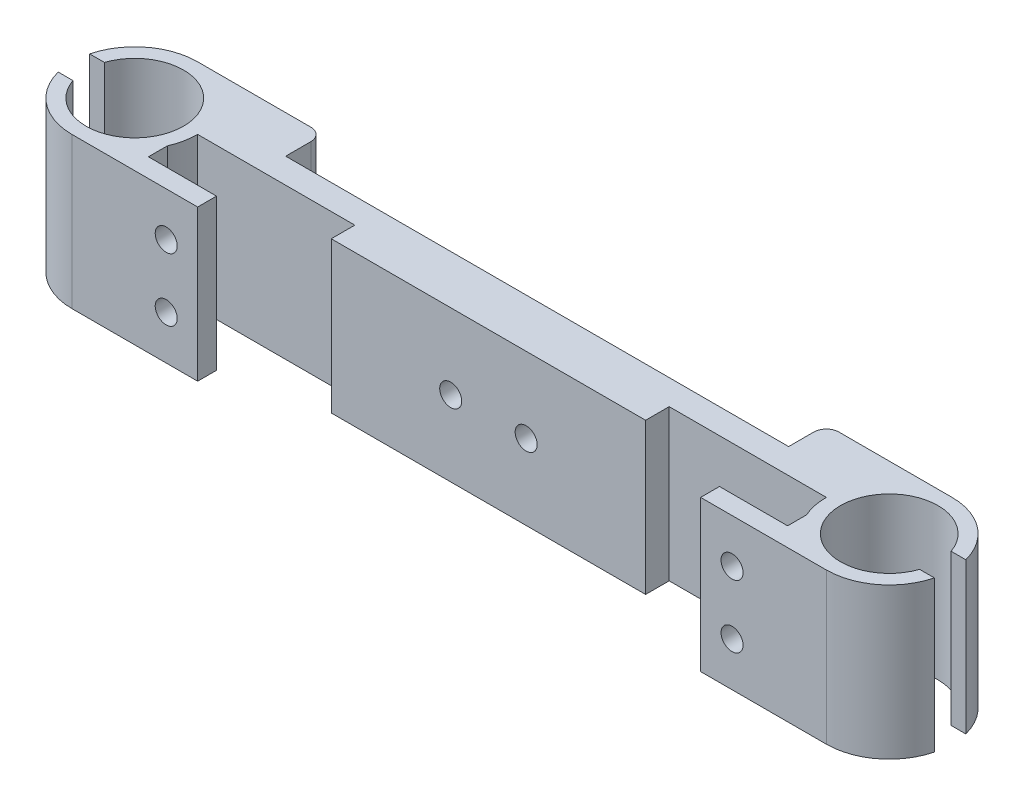
SolidWorks part; units mm, degrees
ref_plane "前视基准面" through (0, 0, 0) normal (0, 0, 1) x (1, 0, 0)
ref_plane "上视基准面" through (0, 0, 0) normal (0, 1, 0) x (1, 0, 0)
ref_plane "右视基准面" through (0, 0, 0) normal (1, 0, 0) x (0, 0, -1)
sketch "草图1" plane through (0, 0, 0) normal (0, 1, 0) x (1, 0, 0)
  line L0 (-50.8348, -4) -> (50.8348, -4)
  line L1 (-60, 0) -> (60, 0) construction
  line L2 (0, 11.701) -> (0, -19.7472) construction
  line L3 (-60, -10) -> (60, -10)
  arc A0 (-50.8348, -4) -> (-60, -10) centre (-60, 0) ccw
  arc A1 (60, -10) -> (50.8348, -4) centre (60, 0) ccw
  circle A2 centre (-60, 0) radius 7.75
  circle A3 centre (60, 0) radius 7.75
  dimension "D1" = 20
  dimension "D2" = 15.5
  dimension "D3" = 120
  dimension "D4" = 15.5
  dimension "D5" = 4
  dimension "D6" = 60
extrude "凸台-拉伸1" add sketch "草图1" along normal blind 24
sketch "草图2" plane through (0, 24, 0) normal (0, 1, 0) x (1, 0, 0)
  line L0 (-50, 0) -> (50, 0)
  line L1 (-60, 10) -> (60, 10)
  arc A0 (-50.8348, -4) -> (-60, -10) centre (-60, 0) ccw construction
  arc A1 (60, -10) -> (50.8348, -4) centre (60, 0) ccw construction
  circle A2 centre (-60, 0) radius 10
  circle A3 centre (60, 0) radius 10
  arc M3 (-50.8348, -4) -> (-60, -10) centre (-60, 0) ccw
  arc M5 (60, -10) -> (50.8348, -4) centre (60, 0) ccw
  dimension "D1" = 20
extrude "凸台-拉伸2" add sketch "草图2" against normal up to surface (24 mm away) contours L1 L0 M3 M5 up to face at (0, 0, -0.6833)
sketch "草图3" plane through (0, 0, 0) normal (0, -1, 0) x (1, 0, 0)
  line L0 (50, 0) -> (-50, 0) construction
  line L1 (25, 0) -> (-25, 0)
  line L2 (25, 0) -> (25, 3.75)
  line L3 (25, 3.75) -> (-25, 3.75)
  line L4 (-25, 0) -> (-25, 3.75)
  dimension "D1" = 50
  dimension "D2" = 25
  dimension "D3" = 3.75
extrude "凸台-拉伸3" add sketch "草图3" against normal blind 24
sketch "草图4" plane through (0, 0, 0) normal (0, -1, 0) x (1, 0, 0)
  line L0 (50.8348, 4) -> (-50.8348, 4) construction
  line L1 (40, 4) -> (-40, 4)
  line L2 (40, 4) -> (40, 10)
  line L3 (40, 10) -> (-40, 10)
  line L4 (-40, 4) -> (-40, 10)
  line L5 (-60, 10) -> (60, 10) construction
  line L6 (60, -10) -> (-60, -10) construction
  line L7 (40, -10) -> (-40, -10)
  line L8 (40, -10) -> (40, -4)
  line L9 (40, -4) -> (-40, -4)
  line L10 (-40, -10) -> (-40, -4)
  line L11 (-25, 0) -> (-50, 0) construction
  dimension "D1" = 80
  dimension "D2" = 40
  dimension "D3" = 80
  dimension "D4" = 4
extrude "切除-拉伸1" cut sketch "草图4" against normal blind 24
fillet "圆角1" radius 2 2 edges at (-40, 12, -10) (40, 12, -10)
sketch "草图5" plane through (0, 0, 0) normal (0, -1, 0) x (1, 0, 0)
  line L0 (67.75, 0) -> (-70, 0) construction
  line L1 (0, -0.3543) -> (0, -8.2573) construction
  line L2 (72.0018, -2.5) -> (64.249, -2.5)
  line L3 (72.0018, -2.5) -> (72.0018, 2.5)
  line L4 (72.0018, 2.5) -> (64.249, 2.5)
  line L5 (64.249, -2.5) -> (64.249, 2.5)
  line L6 (-64.249, -2.5) -> (-64.249, 2.5)
  line L7 (-72.0018, 2.5) -> (-64.249, 2.5)
  line L8 (-72.0018, -2.5) -> (-72.0018, 2.5)
  line L9 (-72.0018, -2.5) -> (-64.249, -2.5)
  circle A0 centre (60, 0) radius 7.75 construction
  arc A1 (-60, 10) -> (-60, -10) centre (-60, 0) ccw construction
  dimension "D1" = 5
  dimension "D2" = 2.5
extrude "切除-拉伸2" cut sketch "草图5" against normal blind 24
sketch "草图6" plane through (0, 0, -4) normal (0, 0, -1) x (-1, 0, 0)
  line L0 (-40, 0) -> (40, 0) construction
  circle A0 centre (-6, 12) radius 1.75
  circle A1 centre (6, 12) radius 1.75
  dimension "D1" = 3.5
  dimension "D2" = 3.5
  dimension "D3" = 12
  dimension "D4" = 12
  dimension "D5" = 12
  dimension "D6" = 6
extrude "切除-拉伸3" cut sketch "草图6" against normal blind 24
sketch "草图7" plane through (0, 0, 10) normal (0, 0, 1) x (1, 0, 0)
  line L0 (40, 24) -> (40, 0) construction
  circle A0 centre (45, 7) radius 1.75
  circle A1 centre (45, 17) radius 1.75
  point P6 (40, 12)
  dimension "D1" = 10
  dimension "D2" = 5
  dimension "D3" = 5
  dimension "D4" = 3.5
  dimension "D5" = 3.5
extrude "切除-拉伸4" cut sketch "草图7" against normal blind 3
sketch "草图8" plane through (0, 0, 0) normal (0, -1, 0) x (1, 0, 0)
  line L0 (40, 4) -> (40, 10) construction
  line L1 (50.8348, 4) -> (40, 4)
  line L2 (50.8348, 4) -> (50.8348, 7)
  line L3 (50.8348, 7) -> (40, 7)
  line L4 (40, 4) -> (40, 7)
  line L5 (-40, 10) -> (-40, 4) construction
  line L6 (-50.8348, 4) -> (-40, 4)
  line L7 (-50.8348, 4) -> (-50.8348, 7)
  line L8 (-50.8348, 7) -> (-40, 7)
  line L9 (-40, 4) -> (-40, 7)
extrude "切除-拉伸5" cut sketch "草图8" against normal through all
sketch "草图9" plane through (0, 0, 10) normal (0, 0, 1) x (1, 0, 0)
  line L0 (-40, 24) -> (-40, 0) construction
  line L1 (-60, 24) -> (-40, 24) construction
  circle A0 centre (-45, 7) radius 1.75
  circle A1 centre (-45, 17) radius 1.75
  point P6 (-40, 12)
  dimension "D1" = 10
  dimension "D2" = 5
  dimension "D3" = 5
  dimension "D4" = 5
  dimension "D5" = 3.5
  dimension "D6" = 7
  dimension "D7" = 3.5
extrude "切除-拉伸6" cut sketch "草图9" against normal blind 3
sketch "草图10" plane through (0, 0, -4) normal (0, 0, -1) x (-1, 0, 0)
  circle A0 centre (6, 12) radius 3
  circle A1 centre (-6, 12) radius 3
  dimension "D1" = 6
  dimension "D2" = 6
extrude "切除-拉伸7" cut sketch "草图10" against normal up to surface (4 mm away) up to face at (-37.5, 12, 0)
